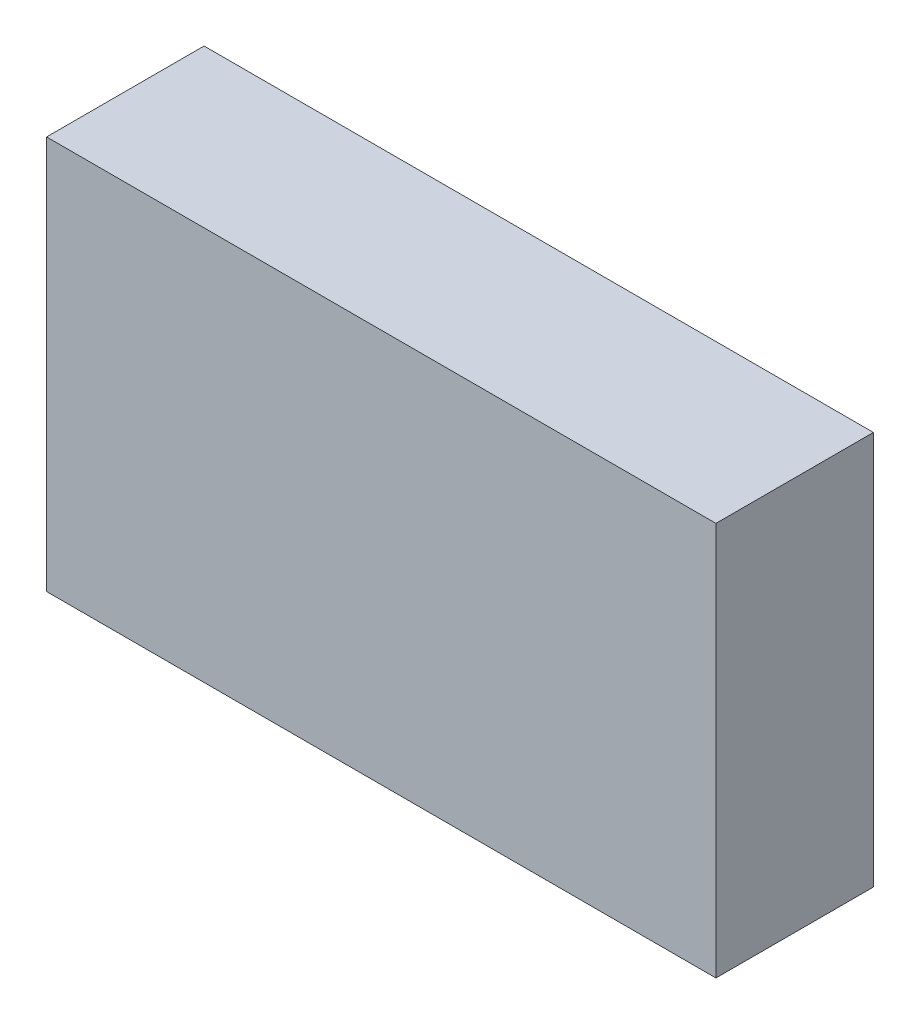
SolidWorks part; units mm, degrees
ref_plane "Front Plane" through (0, 0, 0) normal (0, 0, 1) x (1, 0, 0)
ref_plane "Top Plane" through (0, 0, 0) normal (0, 1, 0) x (1, 0, 0)
ref_plane "Right Plane" through (0, 0, 0) normal (1, 0, 0) x (0, 0, -1)
other "Configuration Table"
sketch "Sketch1" plane through (0, 0, 0) normal (0, 0, 1) x (1, 0, 0)
  line L1 (950, 1690) -> (1120, 1690)
  line L2 (950, 1690) -> (950, 1790)
  line L3 (950, 1790) -> (1120, 1790)
  line L4 (1120, 1690) -> (1120, 1790)
extrude "STORE_PLC_giris_modulu_16_kanal_1" add sketch "Sketch1" against normal blind 40 from offset 660 separate body
